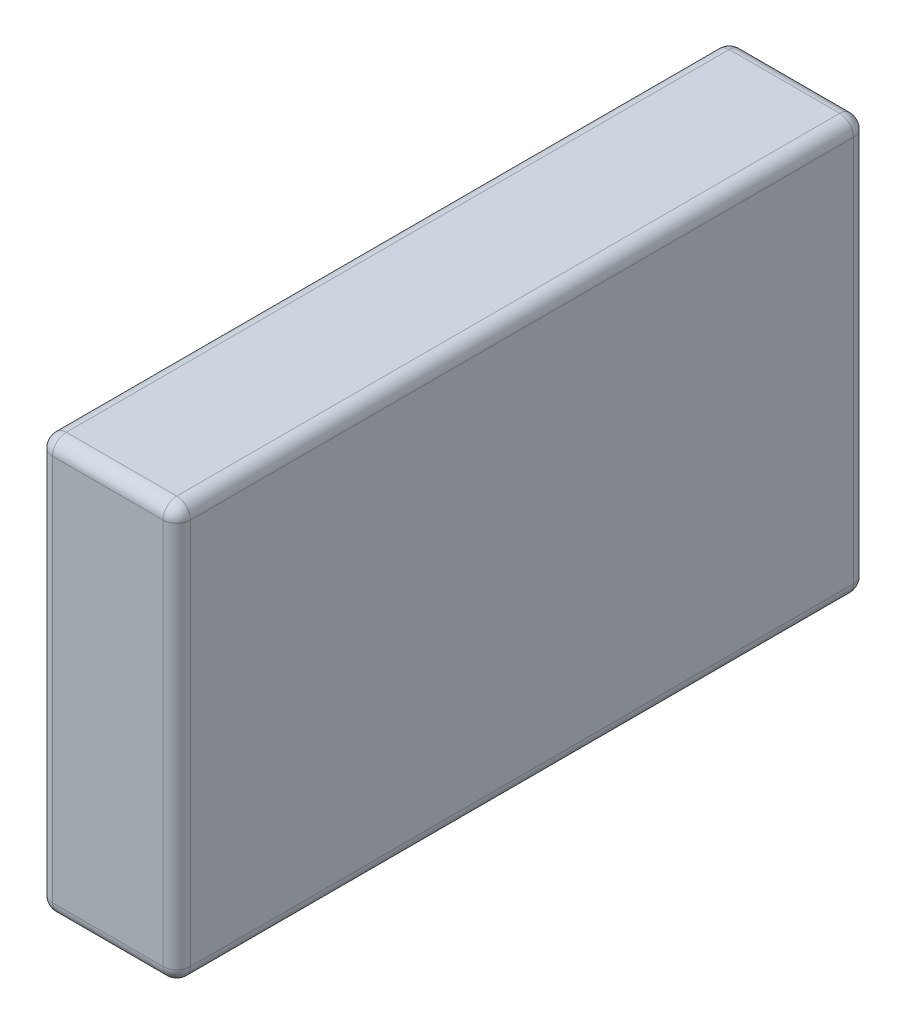
SolidWorks part; units mm, degrees
material "ABS"
ref_plane "Front Plane" through (0, 0, 0) normal (0, 0, 1) x (1, 0, 0)
ref_plane "Top Plane" through (0, 0, 0) normal (0, 1, 0) x (1, 0, 0)
ref_plane "Right Plane" through (0, 0, 0) normal (1, 0, 0) x (0, 0, -1)
sketch "Sketch1" plane through (0, 0, 0) normal (0, 0, 1) x (1, 0, 0)
  line L1 (-4.6902, 2.0513) -> (5.3098, 2.0513)
  line L2 (-4.6902, 2.0513) -> (-4.6902, -27.9487)
  line L3 (-4.6902, -27.9487) -> (5.3098, -27.9487)
  line L4 (5.3098, 2.0513) -> (5.3098, -27.9487)
  dimension "D1" = 10
  dimension "D2" = 30
extrude "Boss-Extrude1" add sketch "Sketch1" along normal blind 50
fillet "Fillet1" radius 1 12 edges at (-4.6902, -12.9487, 50) (-4.6902, -27.9487, 25) (-4.6902, -12.9487, 0) (-4.6902, 2.0513, 25) (0.3098, 2.0513, 0) (0.3098, 2.0513, 50) (0.3098, -27.9487, 50) (0.3098, -27.9487, 0) (5.3098, -27.9487, 25) (5.3098, -12.9487, 0) (5.3098, -12.9487, 50) (5.3098, 2.0513, 25)
